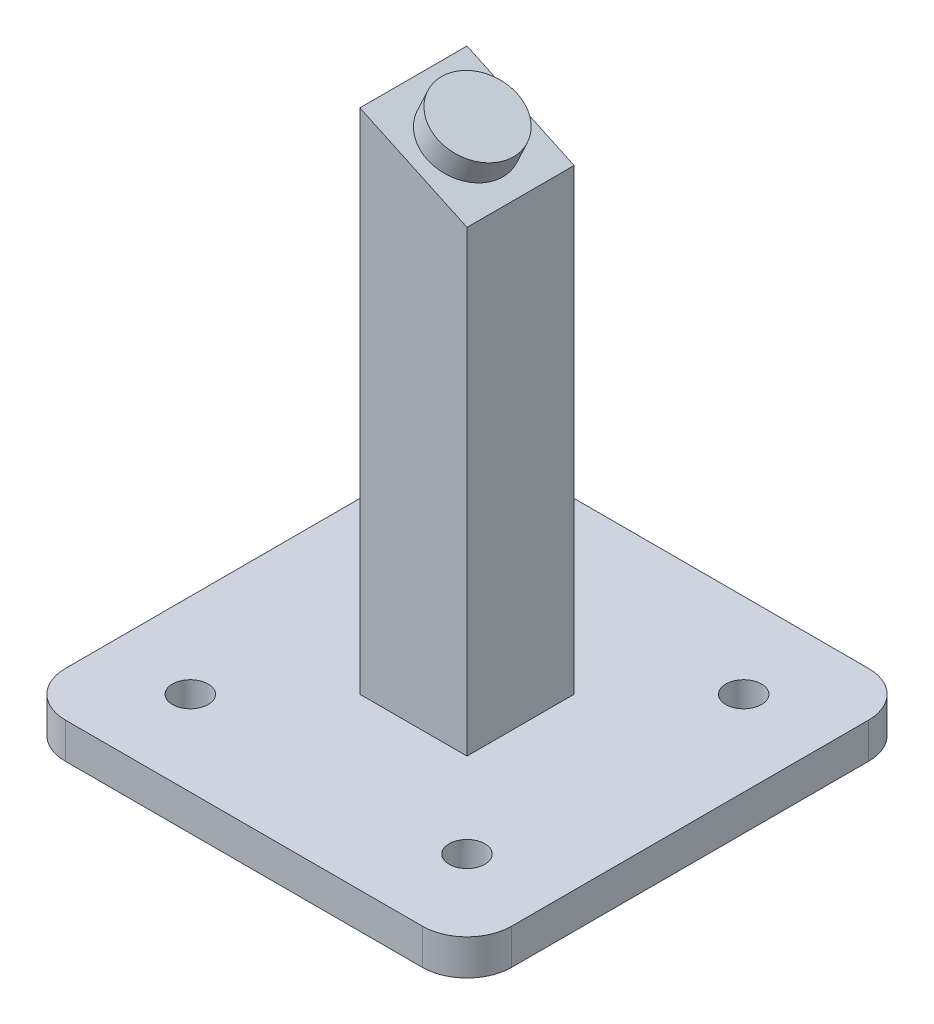
SolidWorks part; units mm, degrees
ref_plane "Front Plane" through (0, 0, 0) normal (0, 0, 1) x (1, 0, 0)
ref_plane "Top Plane" through (0, 0, 0) normal (0, 1, 0) x (1, 0, 0)
ref_plane "Right Plane" through (0, 0, 0) normal (1, 0, 0) x (0, 0, -1)
sketch "Sketch1" plane through (0, 0, 0) normal (0, 1, 0) x (1, 0, 0)
  line L0 (25, 31) -> (25, 19) construction
  line L1 (5, 0) -> (45, 0)
  line L2 (0, 5) -> (0, 45)
  line L3 (5, 50) -> (45, 50)
  line L4 (50, 5) -> (50, 45)
  line L5 (19, 19) -> (31, 19) construction
  line L6 (19, 19) -> (19, 31) construction
  line L7 (19, 31) -> (31, 31) construction
  line L8 (31, 19) -> (31, 31) construction
  line L9 (19, 25) -> (31, 25) construction
  line L10 (9.5, 9.5) -> (9.5, 40.5) construction
  line L11 (9.5, 40.5) -> (40.5, 40.5) construction
  line L12 (40.5, 40.5) -> (40.5, 9.5) construction
  line L13 (40.5, 9.5) -> (9.5, 9.5) construction
  arc A0 (45, 50) -> (50, 45) centre (45, 45) cw
  arc A1 (45, 0) -> (50, 5) centre (45, 5) ccw
  arc A2 (5, 0) -> (0, 5) centre (5, 5) cw
  arc A3 (0, 45) -> (5, 50) centre (5, 45) cw
  circle A4 centre (9.5, 9.5) radius 2
  circle A5 centre (9.5, 40.5) radius 2
  circle A6 centre (40.5, 40.5) radius 2
  circle A7 centre (40.5, 9.5) radius 2
  point P11 (0, 0)
  point P14 (0, 50)
  point P31 (0, 0)
  point P32 (0, 0)
  point P33 (0, 0)
  point P34 (0, 0)
  point P35 (0, 0)
  point P36 (25, 31)
  point P37 (31, 25)
  point P38 (0, 0)
  point P39 (0, 0)
  dimension "D2" = 5
  dimension "D4" = 4
  dimension "D1" = 50
  dimension "D3" = 12
extrude "Boss-Extrude1" add sketch "Sketch1" along normal blind 4
sketch "Sketch3" plane through (0, 4, 0) normal (0, 1, 0) x (1, 0, 0)
  line L1 (19, 31) -> (31, 31)
  line L2 (19, 31) -> (19, 19)
  line L3 (19, 19) -> (31, 19)
  line L4 (31, 31) -> (31, 19)
  point P4 (0, 0)
  point P5 (0, 0)
  point P7 (0, 0)
extrude "Boss-Extrude3" add sketch "Sketch3" along normal blind 51.3
sketch "Sketch5" plane through (0, 0, -19) normal (0, 0, 1) x (1, 0, 0)
  line L0 (31, 55.3) -> (19, 60.8957)
  line L1 (19, 60.8957) -> (19, 55.3)
  line L2 (19, 55.3) -> (31, 55.3)
  dimension "D1" = 25
extrude "Boss-Extrude4" add sketch "Sketch5" against normal up to surface (12 mm away) up to face at (25, 29.65, -31)
sketch "Sketch6" plane through (26.7179, 57.2968, 0) normal (0.4226, 0.9063, 0) x (0.9063, -0.4226, 0)
  line L0 (-1.8955, 25) -> (-8.5158, 25) construction
  line L1 (-8.5158, 31) -> (-8.5158, 19) construction
  line L2 (-1.8955, 25) -> (-1.8955, 31) construction
  line L3 (-8.5158, 31) -> (4.7248, 31) construction
  circle A0 centre (-1.8955, 25) radius 4.45
  dimension "D1" = 8.9
extrude "Boss-Extrude5" add sketch "Sketch6" along normal blind 2.8
